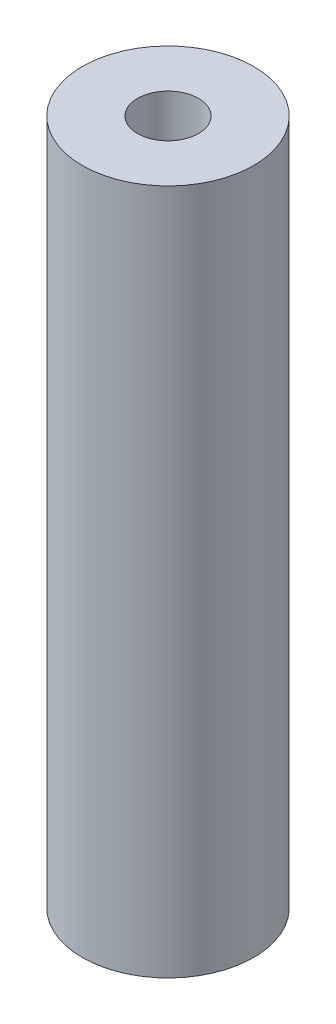
SolidWorks part; units mm, degrees
material "ABS"
ref_plane "Front Plane" through (0, 0, 0) normal (0, 0, 1) x (1, 0, 0)
ref_plane "Top Plane" through (0, 0, 0) normal (0, 1, 0) x (1, 0, 0)
ref_plane "Right Plane" through (0, 0, 0) normal (1, 0, 0) x (0, 0, -1)
sketch "Sketch1" plane through (0, 0, 0) normal (0, 1, 0) x (1, 0, 0)
  circle A0 centre (0, 0) radius 4.5
  dimension "D1" = 9
extrude "Boss-Extrude1" add sketch "Sketch1" along normal mid plane 36
hole_wizard "M3 Clearance Hole1" positions "Sketch2" profile "Sketch3" hole size "M3" standard "ANSI Metric" end condition through all
sketch "Sketch2" plane through (0, 18, 0) normal (0, 1, 0) x (1, 0, 0)
  point P0 (0, 0)
sketch "Sketch3" plane through (0, 18, 0) normal (1, 0, 0) x (0, 0, 1)
  line L0 (0, 0) -> (0, 36)
  line L1 (0, 36) -> (1.6, 36)
  line L2 (1.6, 36) -> (1.6, 0)
  line L5 (1.6, 0) -> (0, 0)
  line L11 (0, -6.35) -> (0, 107.95) construction
  dimension "Thru Hole Dia." = 3.2
  dimension "Thru Hole Depth" = 36
